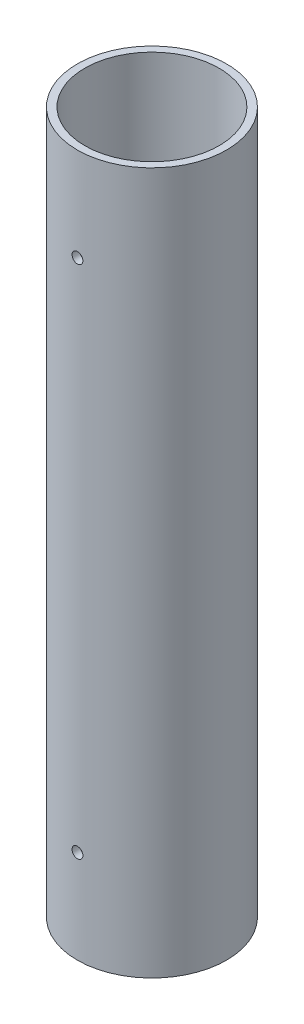
SolidWorks part; units mm, degrees
ref_plane "정면" through (0, 0, 0) normal (0, 0, 1) x (1, 0, 0)
ref_plane "윗면" through (0, 0, 0) normal (0, 1, 0) x (1, 0, 0)
ref_plane "우측면" through (0, 0, 0) normal (1, 0, 0) x (0, 0, -1)
sketch "스케치1" plane through (0, 0, 0) normal (0, 1, 0) x (1, 0, 0)
  circle A0 centre (0, 0) radius 20
  dimension "D1" = 40
extrude "보스-돌출1" add sketch "스케치1" along normal blind 188
sketch "스케치2" plane through (0, 0, 0) normal (0, 1, 0) x (1, 0, 0)
  circle A0 centre (0, 0) radius 18
  dimension "D1" = 36
extrude "컷-돌출2" cut sketch "스케치2" against normal through all and the other way through all
hole_wizard "M2.5 여유 구멍1" positions "스케치4" profile "스케치5" hole size "M2.5" standard "ISO"
sketch "스케치4" plane through (0, 0, 0) normal (0, 0, 1) x (1, 0, 0)
  line L0 (20, 188) -> (-20, 188) construction
  line L1 (20, 188) -> (-20, 188) construction
  line L2 (-20, 0) -> (20, 0) construction
  point P0 (0, 163)
  point P2 (0, 25)
  point P10 (0, 0)
  point P12 (0, 0)
  dimension "D1" = 25
  dimension "D2" = 25
sketch "스케치5" plane through (0, 163, 0) normal (1, 0, 0) x (0, 1, 0)
  line L0 (0, 0) -> (0, 20)
  line L1 (0, 20) -> (1.45, 20)
  line L2 (1.45, 20) -> (1.45, 0)
  line L5 (1.45, 0) -> (0, 0)
  line L11 (0, -6.35) -> (0, 107.95) construction
  dimension "관통 구멍 지름" = 2.9
  dimension "관통 구멍 깊이" = 20
